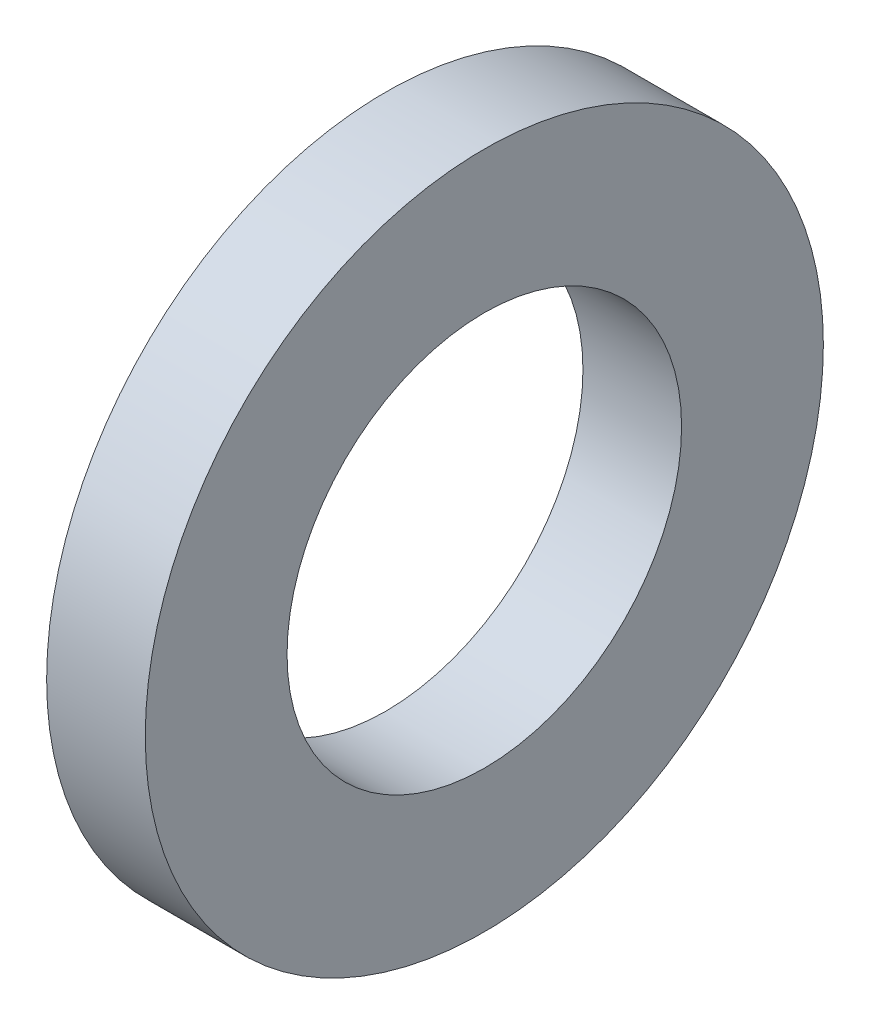
SolidWorks part; units mm, degrees
material "AISI 1020"
ref_plane "Front Plane" through (0, 0, 0) normal (0, 0, 1) x (1, 0, 0)
ref_plane "Top Plane" through (0, 0, 0) normal (0, 1, 0) x (1, 0, 0)
ref_plane "Right Plane" through (0, 0, 0) normal (1, 0, 0) x (0, 0, -1)
sketch "Sketch1" plane through (0, 0, 0) normal (1, 0, 0) x (0, 0, -1)
  circle A0 centre (0, 0) radius 5.5
  circle A1 centre (0, 0) radius 3.2
  dimension "Vidinis d" = 6.4
  dimension "Isorinis d" = 11
extrude "Extrude1" add sketch "Sketch1" along normal blind 1.6
